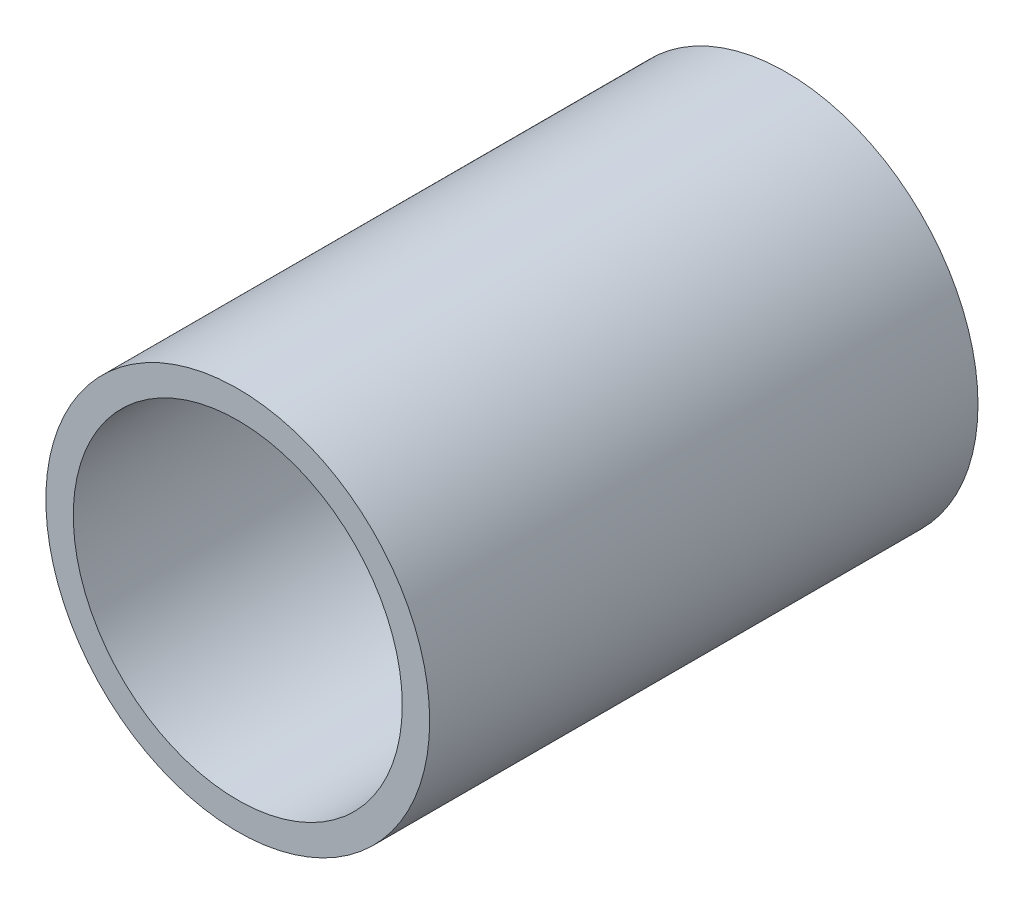
SolidWorks part; units mm, degrees
ref_plane "Front Plane" through (0, 0, 0) normal (0, 0, 1) x (1, 0, 0)
ref_plane "Top Plane" through (0, 0, 0) normal (0, 1, 0) x (1, 0, 0)
ref_plane "Right Plane" through (0, 0, 0) normal (1, 0, 0) x (0, 0, -1)
sketch "Sketch1" plane through (0, 0, 0) normal (0, 0, 1) x (1, 0, 0)
  circle A0 centre (0, 0) radius 8.89
  dimension "D1" = 17.78
extrude "Boss-Extrude1" add sketch "Sketch1" along normal blind 25.4
sketch "Sketch2" plane through (0, 0, 25.4) normal (0, 0, 1) x (1, 0, 0)
  circle A0 centre (0, 0) radius 7.62
  dimension "D1" = 15.24
extrude "Cut-Extrude1" cut sketch "Sketch2" against normal blind 35.306
